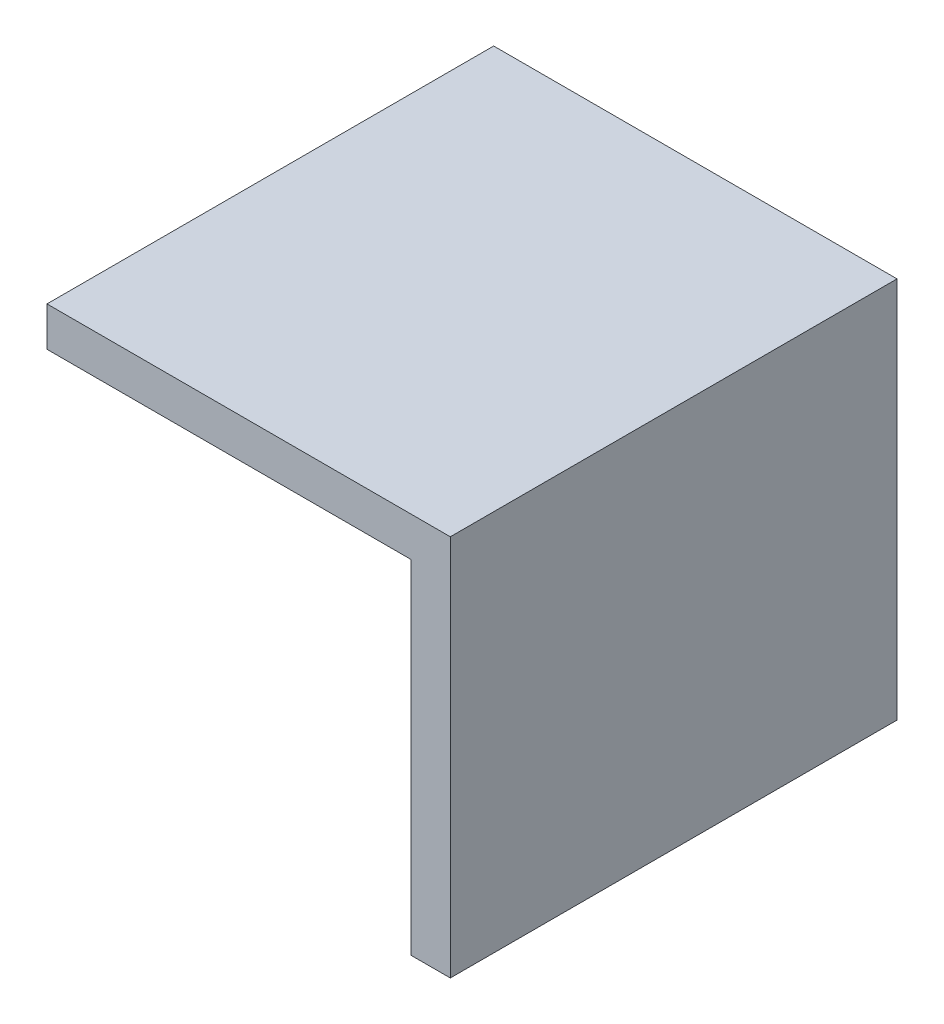
SolidWorks part; units mm, degrees
ref_plane "Front Plane" through (0, 0, 0) normal (0, 0, 1) x (1, 0, 0)
ref_plane "Top Plane" through (0, 0, 0) normal (0, 1, 0) x (1, 0, 0)
ref_plane "Right Plane" through (0, 0, 0) normal (1, 0, 0) x (0, 0, -1)
sketch "Sketch1" plane through (0, 0, 0) normal (0, 1, 0) x (1, 0, 0)
  line L1 (0, 0) -> (40, 0)
  line L2 (0, 0) -> (0, 44.3)
  line L3 (0, 44.3) -> (40, 44.3)
  line L4 (40, 0) -> (40, 44.3)
  dimension "D1" = 40
  dimension "D2" = 44.3
extrude "Boss-Extrude1" add sketch "Sketch1" along normal blind 3.9
sketch "Sketch2" plane through (0, 0, 0) normal (0, -1, 0) x (1, 0, 0)
  line L0 (40, -44.3) -> (0, -44.3) construction
  line L1 (40, 0) -> (36.1, 0)
  line L2 (40, 0) -> (40, -44.3)
  line L3 (40, -44.3) -> (36.1, -44.3)
  line L4 (36.1, 0) -> (36.1, -44.3)
  dimension "D1" = 3.9
extrude "Boss-Extrude2" add sketch "Sketch2" along normal blind 33.996 contours L4 L3 L2 L1
